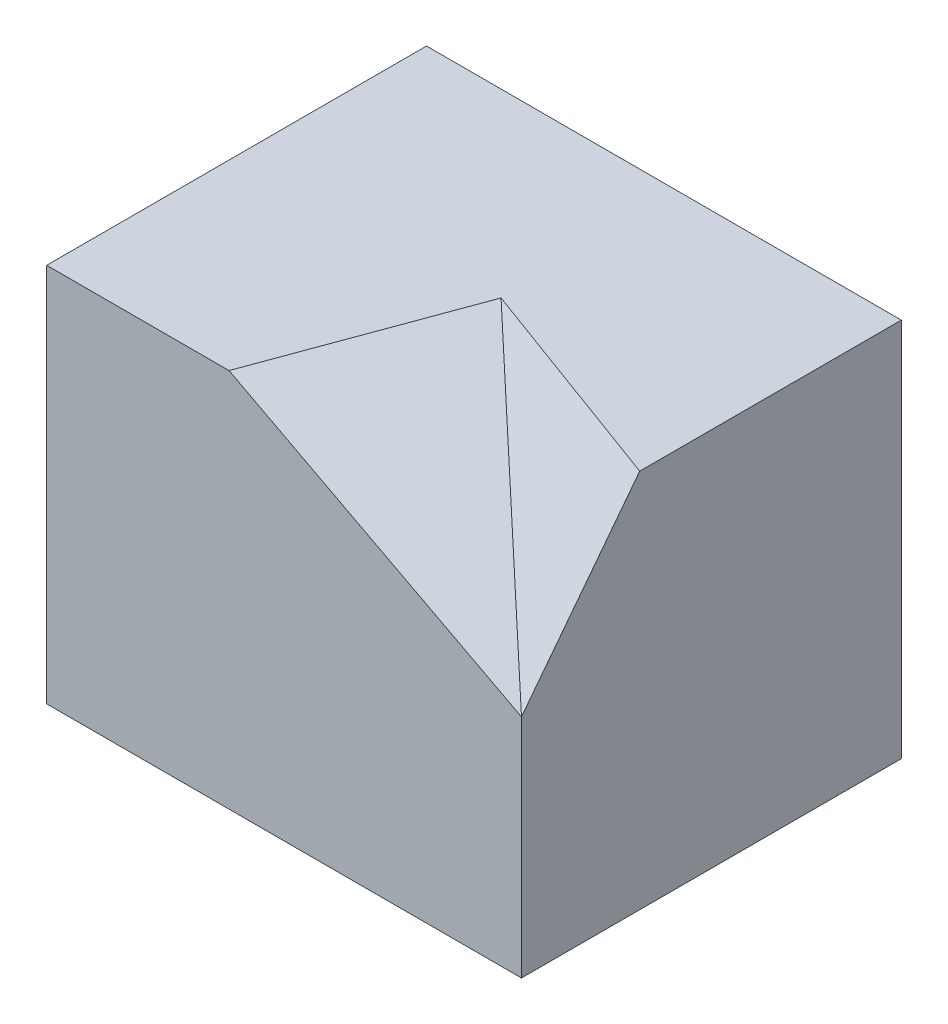
SolidWorks part; units mm, degrees
ref_plane "Front Plane" through (0, 0, 0) normal (0, 0, 1) x (1, 0, 0)
ref_plane "Top Plane" through (0, 0, 0) normal (0, 1, 0) x (1, 0, 0)
ref_plane "Right Plane" through (0, 0, 0) normal (1, 0, 0) x (0, 0, -1)
sketch "Sketch1" plane through (0, 0, 0) normal (0, 1, 0) x (1, 0, 0)
  line L1 (0, 0) -> (1270, 0)
  line L2 (0, 0) -> (0, 1016)
  line L3 (0, 1016) -> (1270, 1016)
  line L4 (1270, 0) -> (1270, 1016)
  dimension "D1" = 1016
  dimension "D2" = 1270
extrude "Boss-Extrude1" add sketch "Sketch1" along normal blind 1016
sketch "Sketch2" plane through (0, 1016, 0) normal (0, 1, 0) x (1, 0, 0)
  line L0 (487.6977, 0) -> (683.3419, 532.0141)
  line L1 (0, 0) -> (1270, 0) construction
  line L2 (683.3419, 532.0141) -> (1270, 316.275)
  line L3 (1270, 0) -> (1270, 1016) construction
  line L4 (487.6977, 0) -> (1270, 0)
  line L5 (1270, 0) -> (1270, 316.275)
sketch "Sketch4" plane through (0, 0, 0) normal (0, 0, 1) x (1, 0, 0)
  line L0 (1270, 1016) -> (1270, 0) construction
  point P0 (1270, 605.0565)
loft "Cut-Loft3" cut profiles "Sketch2", "Sketch4"
